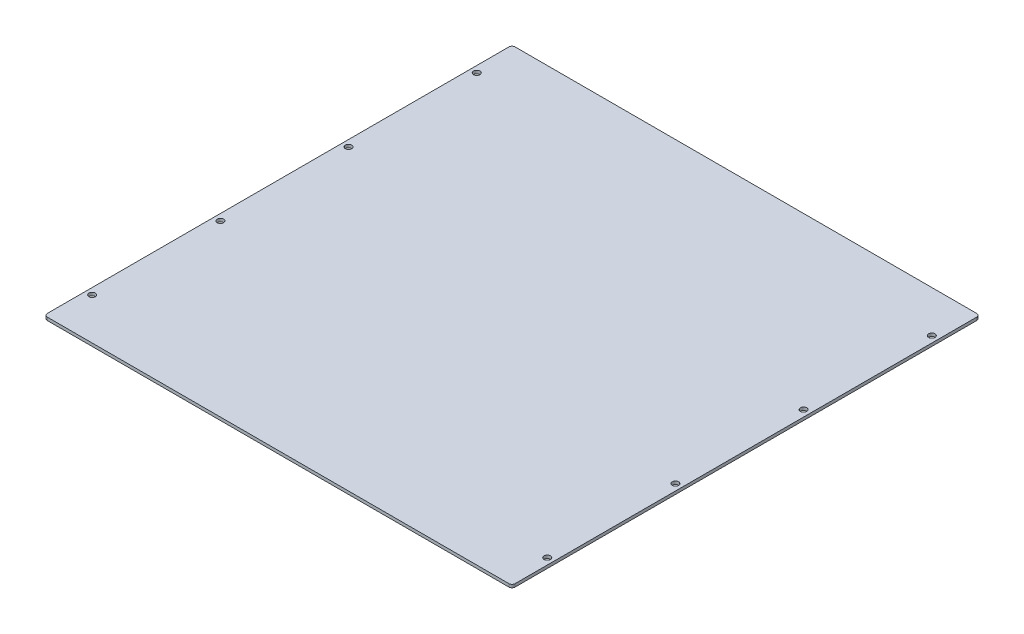
SolidWorks part; units mm, degrees
material "PC High Viscosity"
ref_plane "Front Plane" through (0, 0, 0) normal (0, 0, 1) x (1, 0, 0)
ref_plane "Top Plane" through (0, 0, 0) normal (0, 1, 0) x (1, 0, 0)
ref_plane "Right Plane" through (0, 0, 0) normal (1, 0, 0) x (0, 0, -1)
sketch "Sketch1" plane through (0, 0, 0) normal (0, 1, 0) x (1, 0, 0)
  line L1 (-231.775, 231.775) -> (231.775, 231.775)
  line L2 (-231.775, 231.775) -> (-231.775, -231.775)
  line L3 (-231.775, -231.775) -> (231.775, -231.775)
  line L4 (231.775, 231.775) -> (231.775, -231.775)
  line L5 (-231.775, 231.775) -> (231.775, -231.775) construction
  line L6 (-231.775, -231.775) -> (231.775, 231.775) construction
  point P0 (0, 0)
  dimension "D1" = 463.55
  dimension "D2" = 463.55
extrude "Boss-Extrude1" add sketch "Sketch1" along normal blind 2.9972
fillet "Fillet1" radius 3.175 4 edges at (-231.775, 1.4986, -231.775) (231.775, 1.4986, -231.775) (231.775, 1.4986, 231.775) (-231.775, 1.4986, 231.775)
hole_wizard "1/4 (0.25) Diameter Hole1" positions "Sketch5" profile "Sketch4" hole size "1/4" standard "ANSI Inch" end condition through all
sketch "Sketch5" plane through (0, 2.9972, 0) normal (0, 1, 0) x (1, 0, 0)
  line L3 (-231.775, 228.6) -> (-231.775, -228.6) construction
  line L4 (231.775, -228.6) -> (231.775, 228.6) construction
  point P46 (-225.425, 190.5)
  point P57 (225.425, 190.5)
  point P58 (225.425, 63.5)
  point P59 (225.425, -63.5)
  point P60 (225.425, -190.5)
  point P61 (-225.425, 63.5)
  point P62 (-225.425, -63.5)
  point P63 (-225.425, -190.5)
  dimension "D2" = 6.35
  dimension "D5" = 127
  dimension "D6" = 6.35
  dimension "D1" = 63.5
  dimension "D3" = 2
  dimension "D4" = 4
sketch "Sketch4" plane through (-225.425, 2.9972, -190.5) normal (1, 0, 0) x (0, 0, 1)
  line L0 (0, 0) -> (0, 2.9972)
  line L1 (0, 2.9972) -> (3.175, 2.9972)
  line L2 (3.175, 2.9972) -> (3.175, 0)
  line L5 (3.175, 0) -> (0, 0)
  line L11 (0, -6.35) -> (0, 107.95) construction
  dimension "Thru Hole Dia." = 6.35
  dimension "Thru Hole Depth" = 2.9972
equation "\"D1@Sketch5\"=\"D5@Sketch5\"/2"
